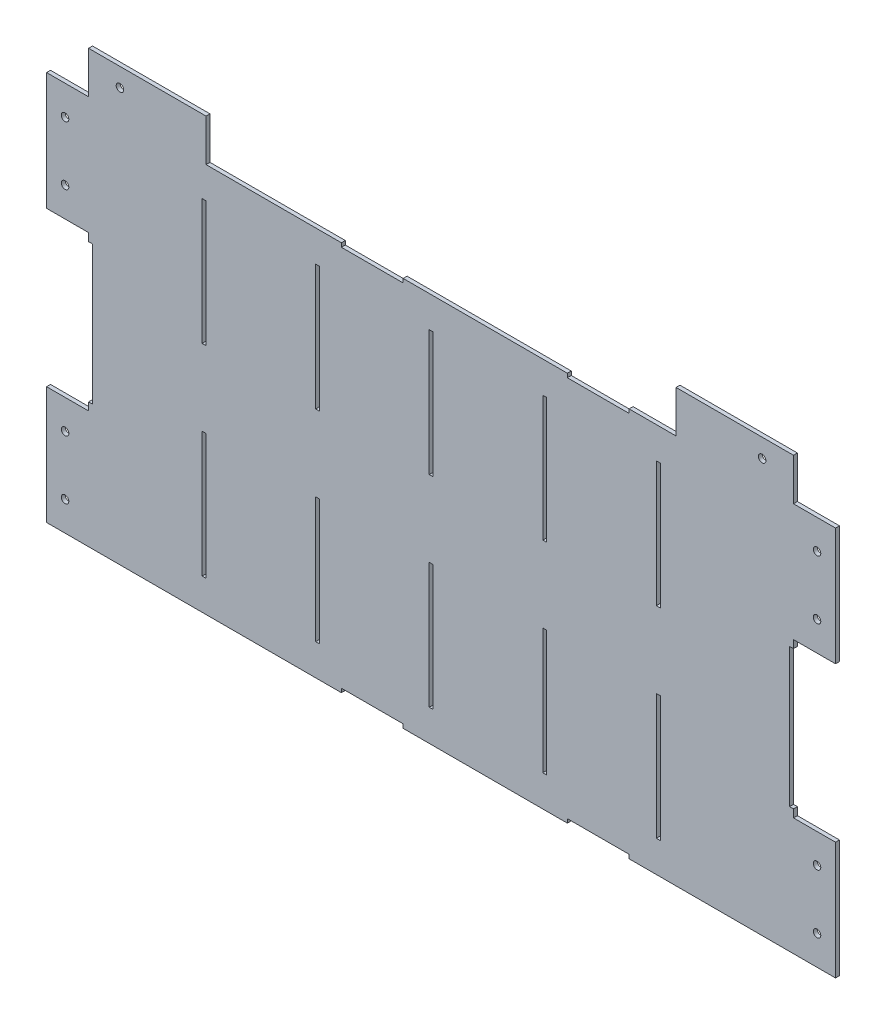
SolidWorks part; units mm, degrees
material "6061-T6 (SS)"
ref_plane "X-Y Datum" through (0, 0, 0) normal (0, 0, 1) x (1, 0, 0)
ref_plane "X-Z Datum" through (0, 0, 0) normal (0, 1, 0) x (1, 0, 0)
ref_plane "Y-Z Datum" through (0, 0, 0) normal (1, 0, 0) x (0, 0, -1)
sketch "Sketch1" plane through (0, 0, 0) normal (0, 0, 1) x (1, 0, 0)
  line L0 (-285.4305, 0) -> (285.4305, 0) construction
  line L1 (-285.4305, -157.7875) -> (285.4305, -157.7875)
  line L2 (-285.4305, -157.7875) -> (-285.4305, 157.7875)
  line L3 (-285.4305, 157.7875) -> (285.4305, 157.7875)
  line L4 (285.4305, -157.7875) -> (285.4305, 157.7875)
  line L5 (-285.4305, -157.7875) -> (285.4305, 157.7875) construction
  line L6 (-285.4305, 157.7875) -> (285.4305, -157.7875) construction
  line L7 (-282.2555, -154.615) -> (-282.2555, 154.615)
  line L8 (-280.6655, -153.025) -> (-195.0655, -153.025)
  line L9 (-280.6655, -153.025) -> (-280.6655, 153.025)
  line L10 (-280.6655, 153.025) -> (-195.0655, 153.025)
  line L11 (-195.0655, -153.025) -> (-195.0655, 153.025)
  line L12 (-280.6655, -153.025) -> (-195.0655, 153.025) construction
  line L13 (-280.6655, 153.025) -> (-195.0655, -153.025) construction
  line L14 (-282.2555, 154.615) -> (-193.4755, 154.615)
  line L15 (-193.4755, -154.615) -> (-193.4755, 154.615)
  line L16 (-282.2555, -154.615) -> (-193.4755, -154.615)
  line L17 (-190.3005, 154.615) -> (-101.5205, 154.615)
  line L18 (-188.7105, 153.025) -> (-103.1105, 153.025)
  line L19 (-190.3005, -154.615) -> (-190.3005, 154.615)
  line L20 (-188.7105, -153.025) -> (-188.7105, 153.025)
  line L21 (-101.5205, -154.615) -> (-101.5205, 154.615)
  line L22 (-103.1105, -153.025) -> (-103.1105, 153.025)
  line L23 (-188.7105, -153.025) -> (-103.1105, -153.025)
  line L24 (-190.3005, -154.615) -> (-101.5205, -154.615)
  line L25 (-188.7105, -153.025) -> (-103.1105, 153.025) construction
  line L26 (-188.7105, 153.025) -> (-103.1105, -153.025) construction
  line L27 (-98.3455, 154.615) -> (-9.5655, 154.615)
  line L28 (-96.7555, 153.025) -> (-11.1555, 153.025)
  line L29 (-98.3455, -154.615) -> (-98.3455, 154.615)
  line L30 (-96.7555, -153.025) -> (-96.7555, 153.025)
  line L31 (-9.5655, -154.615) -> (-9.5655, 154.615)
  line L32 (-11.1555, -153.025) -> (-11.1555, 153.025)
  line L33 (-96.7555, -153.025) -> (-11.1555, -153.025)
  line L34 (-98.3455, -154.615) -> (-9.5655, -154.615)
  line L35 (-96.7555, -153.025) -> (-11.1555, 153.025) construction
  line L36 (-96.7555, 153.025) -> (-11.1555, -153.025) construction
  line L37 (-6.3905, 154.615) -> (82.3895, 154.615)
  line L38 (-4.8005, 153.025) -> (80.7995, 153.025)
  line L39 (-6.3905, -154.615) -> (-6.3905, 154.615)
  line L40 (-4.8005, -153.025) -> (-4.8005, 153.025)
  line L41 (82.3895, -154.615) -> (82.3895, 154.615)
  line L42 (80.7995, -153.025) -> (80.7995, 153.025)
  line L43 (-4.8005, -153.025) -> (80.7995, -153.025)
  line L44 (-6.3905, -154.615) -> (82.3895, -154.615)
  line L45 (-4.8005, -153.025) -> (80.7995, 153.025) construction
  line L46 (-4.8005, 153.025) -> (80.7995, -153.025) construction
  line L47 (85.5645, 154.615) -> (174.3445, 154.615)
  line L48 (87.1545, 153.025) -> (172.7545, 153.025)
  line L49 (85.5645, -154.615) -> (85.5645, 154.615)
  line L50 (87.1545, -153.025) -> (87.1545, 153.025)
  line L51 (174.3445, -154.615) -> (174.3445, 154.615)
  line L52 (172.7545, -153.025) -> (172.7545, 153.025)
  line L53 (87.1545, -153.025) -> (172.7545, -153.025)
  line L54 (85.5645, -154.615) -> (174.3445, -154.615)
  line L55 (87.1545, -153.025) -> (172.7545, 153.025) construction
  line L56 (87.1545, 153.025) -> (172.7545, -153.025) construction
  point P0 (0, 0)
  point P8 (-237.8655, 0)
  point P17 (-145.9105, 0)
  dimension "D1" = 570.861
  dimension "D2" = 315.575
  dimension "D3" = 306.05
  dimension "D4" = 85.6
  dimension "D5" = 3.175
  dimension "D8" = 3.175
  dimension "D9" = 91.955
  dimension "D6" = 1.59
  dimension "D7" = 5
extrude "Boss-Extrude1" add sketch "Sketch1" along normal blind 3.175
sketch "Sketch2" plane through (0, 0, 3.175) normal (0, 0, 1) x (1, 0, 0)
  line L0 (-190.3005, -154.615) -> (-193.4755, -154.615) construction
  line L1 (-191.888, -154.615) -> (-191.888, 157.7875) construction
  line L2 (-285.4305, 157.7875) -> (285.4305, 157.7875) construction
  line L4 (-193.4755, -30.7875) -> (-190.3005, -30.7875)
  line L5 (-193.4755, -30.7875) -> (-193.4755, -132.3875)
  line L6 (-193.4755, -132.3875) -> (-190.3005, -132.3875)
  line L7 (-190.3005, -30.7875) -> (-190.3005, -132.3875)
  line L8 (-193.4755, -30.7875) -> (-190.3005, -132.3875) construction
  line L9 (-193.4755, -132.3875) -> (-190.3005, -30.7875) construction
  line L12 (-285.4305, -157.7875) -> (285.4305, -157.7875) construction
  point P8 (-191.888, -81.5875)
  dimension "D1" = 76.2
  dimension "D2" = 3.175
  dimension "D3" = 101.6
extrude "Cut-Extrude1" cut sketch "Sketch2" against normal blind 3.175
sketch "Sketch7" plane through (0, 0, 3.175) normal (0, 0, 1) x (1, 0, 0)
  line L0 (285.4305, -157.7875) -> (285.4305, 157.7875) construction
  line L1 (102.3049, -154.6125) -> (152.3049, -154.6125)
  line L2 (102.3049, -154.6125) -> (102.3049, -157.7875)
  line L3 (102.3049, -157.7875) -> (152.3049, -157.7875)
  line L4 (152.3049, -154.6125) -> (152.3049, -157.7875)
  line L5 (-80.6951, -154.6125) -> (-30.6951, -154.6125)
  line L6 (-80.6951, -154.6125) -> (-80.6951, -157.7875)
  line L7 (-80.6951, -157.7875) -> (-30.6951, -157.7875)
  line L8 (-30.6951, -154.6125) -> (-30.6951, -157.7875)
  dimension "D1" = 133
  dimension "D2" = 50
  dimension "D3" = 3.175
  dimension "D4" = 50
  dimension "D5" = 133.1256
extrude "Cut-Extrude5" cut sketch "Sketch7" against normal blind 3.175
mirror "Mirror3" about plane through (0, 0, 0) normal (0, 1, 0) of "Cut-Extrude1"
pattern_linear "LPattern2" count 5 spacing 91.96 along (1, 0, 0) of "Mirror3", "Cut-Extrude1"
sketch "Sketch9" plane through (0, 0, 0) normal (0, 0, -1) x (-1, 0, 0)
  line L0 (-304.4805, -62.5375) -> (-304.4805, -157.7875) construction
  line L9 (-285.4305, 157.7875) -> (-190.3024, 157.7875)
  line L10 (-285.4305, 157.7875) -> (-285.4305, 191.8235)
  line L11 (-285.4305, 191.8235) -> (-190.3024, 191.8235)
  line L12 (-190.3024, 157.7875) -> (-190.3024, 191.8235)
  line L13 (-285.4305, 157.7875) -> (-323.5305, 157.7875)
  line L14 (-285.4305, 157.7875) -> (-285.4305, 62.5375)
  line L15 (-285.4305, 62.5375) -> (-323.5305, 62.5375)
  line L18 (-323.5305, 110.1625) -> (-285.4305, 110.1625) construction
  line L20 (-285.4305, -157.7875) -> (-323.5305, -157.7875)
  line L26 (-285.4305, -62.5375) -> (-323.5305, -62.5375)
  line L28 (-323.5305, -106.9875) -> (-323.5305, -157.7875) construction
  line L29 (-323.5305, -106.9875) -> (-285.4305, -106.9875) construction
  line L30 (-304.4805, -62.5375) -> (-304.4805, -110.1625) construction
  line L31 (-304.4805, -110.1625) -> (-304.4805, -157.7875) construction
  line L32 (-304.4805, -62.5375) -> (-304.4805, -110.1625) construction
  line L33 (-304.4805, -110.1625) -> (-304.4805, -157.7875) construction
  line L35 (-323.5305, 62.5375) -> (-323.5305, 157.7875) construction
  line L36 (-319.4665, 157.7875) -> (-319.4665, 62.5375)
  line L37 (-323.5305, -62.5375) -> (-323.5305, -157.7875) construction
  line L40 (-304.4805, 157.7875) -> (-304.4805, 110.1625) construction
  line L41 (-304.4805, 110.1625) -> (-304.4805, 62.5375) construction
  line L42 (-319.4665, -62.5375) -> (-319.4665, -157.7875)
  line L43 (-304.4805, 110.1625) -> (-304.4805, 62.5375) construction
  line L44 (-304.4805, -62.5375) -> (-304.4805, -110.1625) construction
  line L45 (-304.4805, -110.1625) -> (-304.4805, -157.7875) construction
  line L46 (-285.4305, -62.5375) -> (-285.4305, -157.7875)
  line L47 (-285.4305, 176.8375) -> (-190.3024, 176.8375) construction
  line L48 (-285.4305, 176.8375) -> (-260.0305, 176.8375) construction
  line L49 (-234.6305, 191.8235) -> (-234.6305, 157.7875) construction
  circle A4 centre (-304.4805, 133.975) radius 3.048
  circle A6 centre (-304.4805, 86.35) radius 3.048
  circle A7 centre (-304.4805, -86.35) radius 3.048
  circle A8 centre (-304.4805, -133.975) radius 3.048
  circle A10 centre (-260.0305, 176.8375) radius 3.048
  point P22 (-307.5285, 133.975)
  point P39 (-260.0305, 179.8855)
  dimension "D1" = 11.938
  dimension "D2" = 95.25
  dimension "D6" = 6.096
  dimension "D7" = 95.25
  dimension "D8" = 6.096
  dimension "D9" = 6.096
  dimension "D10" = 6.096
  dimension "D12" = 19.05
  dimension "D13" = 11.938
  dimension "D11" = 25.4
  dimension "D3" = 95.1281
  dimension "D4" = 34.036
  dimension "D5" = 19.05
  dimension "D14" = 25.4
extrude "Boss-Extrude3" add sketch "Sketch9" against normal blind 3.175
mirror "Mirror4" about plane through (0, 0, 0) normal (1, 0, 0) of "Boss-Extrude3"
mirror "Mirror5" about plane through (0, 0, 0) normal (0, 1, 0) of "Cut-Extrude5"
sketch "Sketch10" plane through (0, 0, 0) normal (0, 0, -1) x (-1, 0, 0)
  line L0 (-285.4305, 62.5375) -> (-285.4305, 56.1875)
  line L1 (-285.4305, -62.5375) -> (-285.4305, 62.5375) construction
  line L2 (-285.4305, -62.5375) -> (-319.4665, -62.5375) construction
  line L3 (-285.4305, 56.1875) -> (-282.2555, 56.1875)
  line L4 (-285.4305, 56.1875) -> (-285.4305, -56.1875)
  line L5 (-285.4305, -56.1875) -> (-282.2555, -56.1875)
  line L6 (-282.2555, 56.1875) -> (-282.2555, -56.1875)
  line L7 (-285.4305, 62.5375) -> (-319.4665, 62.5375) construction
  dimension "D1" = 6.35
  dimension "D2" = 3.175
  dimension "D3" = 6.35
extrude "Cut-Extrude6" cut sketch "Sketch10" against normal through all contours L6 L3 L4 L5
mirror "Mirror6" about plane through (0, 0, 0) normal (1, 0, 0) of "Cut-Extrude6"
